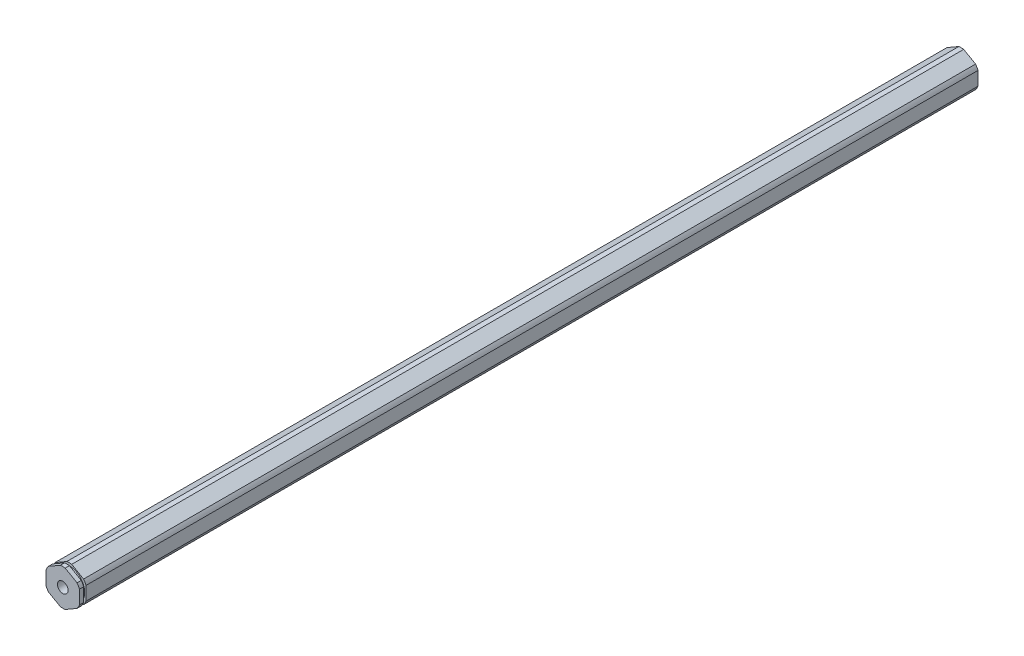
SolidWorks part; units mm, degrees
ref_plane "Front Plane" through (0, 0, 0) normal (0, 0, 1) x (1, 0, 0)
ref_plane "Top Plane" through (0, 0, 0) normal (0, 1, 0) x (1, 0, 0)
ref_plane "Right Plane" through (0, 0, 0) normal (1, 0, 0) x (0, 0, -1)
sketch "Sketch1" plane through (0, 0, 0) normal (0, 0, 1) x (1, 0, 0)
  line L1 (0, 7.3323) -> (-6.35, 3.6662)
  line L2 (-6.35, 3.6662) -> (-6.35, -3.6662)
  line L3 (-6.35, -3.6662) -> (0, -7.3323)
  line L4 (0, -7.3323) -> (6.35, -3.6662)
  line L5 (6.35, -3.6662) -> (6.35, 3.6662)
  line L6 (6.35, 3.6662) -> (0, 7.3323)
  circle A0 centre (0, 0) radius 6.35 construction
  circle A1 centre (0, 0) radius 6.858
  dimension "D1" = 12.7
  dimension "D2" = 13.716
extrude "Boss-Extrude1" add sketch "Sketch1" along normal mid plane 340.614 contours L5 A1 L6 L1 L2 L3 L4
hole_wizard "#10-32 Tapped Hole1" positions "3DSketch1" profile "Sketch2" tap size "#10-32" standard "ANSI Inch"
sketch3d "3DSketch1"
  line L0 (0, 0, 170.307) -> (0, 0, -170.307) construction
  line L1 (0, 0, 170.307) -> (0, 0, -170.307) construction
  point P0 (0, 0, 170.307)
  point P4 (0, 0, -170.307)
sketch "Sketch2" plane through (0, 0, 170.307) normal (1, 0, 0) x (0, -1, 0)
  line L0 (0, 0) -> (0, 17.5608)
  line L1 (0, 17.5608) -> (2.0193, 16.3474)
  line L2 (2.0193, 16.3474) -> (2.0193, 0)
  line L5 (2.0193, 0) -> (0, 0)
  line L10 (0, 17.5608) -> (-2.0193, 16.3474) construction
  line L11 (0, -6.35) -> (0, 107.95) construction
  dimension "Tap Drill Dia." = 4.0386
  dimension "Tap Drill Depth" = 16.3474
  dimension "Drill Angle" = 118
cosmetic thread "Hole Thread1" parameters "D1"=13.97, "D2"=4.826
cosmetic thread "Hole Thread2" parameters "D1"=13.97, "D2"=4.826
sketch "Sketch5" plane through (0, 0, 0) normal (1, 0, 0) x (0, 0, -1)
  line L0 (170.307, 6.858) -> (-170.307, 6.858) construction
  line L1 (-168.7195, 6.858) -> (-167.8305, 6.858)
  line L2 (-168.7195, 6.858) -> (-168.7195, 5.8547)
  line L3 (-168.7195, 5.8547) -> (-167.8305, 5.8547)
  line L4 (-167.8305, 6.858) -> (-167.8305, 5.8547)
  line L5 (-165.0472, 0) -> (-158.8423, 0) construction
  dimension "D1" = 5.8547
  dimension "D2" = 0.889
  dimension "D3" = 1.5875
revolve "Cut-Revolve1" cut sketch "Sketch5" angle 360 about L5
mirror "Mirror1" [suppressed] about plane through (0, 0, 0) normal (0, 0, 1)
